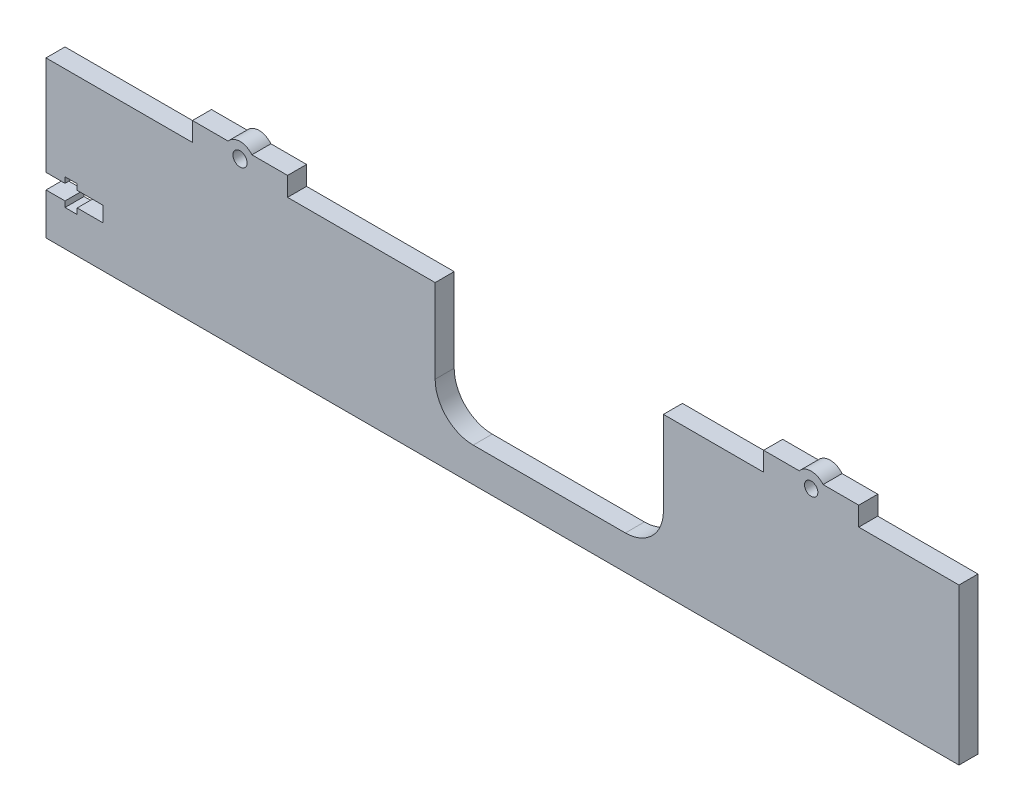
SolidWorks part; units mm, degrees
ref_plane "Front Plane" through (0, 0, 0) normal (0, 0, 1) x (1, 0, 0)
ref_plane "Top Plane" through (0, 0, 0) normal (0, 1, 0) x (1, 0, 0)
ref_plane "Right Plane" through (0, 0, 0) normal (1, 0, 0) x (0, 0, -1)
sketch "Sketch1" plane through (0, 0, 0) normal (0, 0, 1) x (1, 0, 0)
  line L1 (-120, 25.5) -> (120, 25.5)
  line L2 (-120, 25.5) -> (-120, -25.5)
  line L3 (-120, -25.5) -> (120, -25.5)
  line L4 (120, 25.5) -> (120, -25.5)
  dimension "D1" = 240
  dimension "D2" = 51
  dimension "D3" = 25.5
  dimension "D4" = 120
extrude "Boss-Extrude1" add sketch "Sketch1" along normal blind 5
sketch "Sketch4" plane through (0, 0, 5) normal (0, 0, 1) x (1, 0, 0)
  line L0 (120, 25.5) -> (-120, 25.5) construction
  line L1 (-81.5, 25.5) -> (-56.5, 25.5)
  line L2 (-81.5, 25.5) -> (-81.5, 30.5)
  line L3 (-81.5, 30.5) -> (-56.5, 30.5)
  line L4 (-56.5, 25.5) -> (-56.5, 30.5)
  line L5 (-120, 25.5) -> (-120, -25.5) construction
  dimension "D1" = 38.5
  dimension "D2" = 25
  dimension "D3" = 5
extrude "Boss-Extrude2" add sketch "Sketch4" against normal blind 5
sketch "Sketch5" plane through (0, 0, 5) normal (0, 0, 1) x (1, 0, 0)
  line L0 (-120, -25.5) -> (120, -25.5) construction
  line L1 (17.5, -25.5) -> (67.5, -25.5)
  line L2 (17.5, -25.5) -> (17.5, -30.5)
  line L3 (17.5, -30.5) -> (67.5, -30.5)
  line L4 (67.5, -25.5) -> (67.5, -30.5)
  line L5 (120, -25.5) -> (120, 25.5) construction
  line L11 (0, 0) -> (0, -46.5213) construction
  line L12 (-67.5, -25.5) -> (-67.5, -30.5)
  line L13 (-17.5, -30.5) -> (-67.5, -30.5)
  line L14 (-17.5, -25.5) -> (-17.5, -30.5)
  line L15 (-17.5, -25.5) -> (-67.5, -25.5)
  point P10 (67.5, -28)
  dimension "D1" = 52.5
  dimension "D2" = 50
  dimension "D3" = 5
extrude "Boss-Extrude3" [suppressed] add sketch "Sketch5" against normal blind 5
sketch "Sketch6" plane through (0, 0, 5) normal (0, 0, 1) x (1, 0, 0)
  line L13 (0, 0) -> (0, -13.303) construction
  line L14 (-115, -4.5622) -> (-120, -4.5622)
  line L15 (-111.8, -0.5622) -> (-105, -0.5622)
  line L16 (-111.8, -6.0622) -> (-111.8, -4.5622)
  line L17 (-115, -6.0622) -> (-111.8, -6.0622)
  line L18 (-115, -4.5622) -> (-115, -6.0622)
  line L19 (-115, 0.9378) -> (-115, -0.5622)
  line L20 (-111.8, 0.9378) -> (-115, 0.9378)
  line L21 (-111.8, -0.5622) -> (-111.8, 0.9378)
  line L22 (-120, -4.5622) -> (-120, -0.5622)
  line L23 (-105, -4.5622) -> (-111.8, -4.5622)
  line L24 (-105, -0.5622) -> (-105, -4.5622)
  line L25 (-120, -0.5622) -> (-115, -0.5622)
extrude "Cut-Extrude1" cut sketch "Sketch6" against normal blind 10
sketch "Sketch9" plane through (0, 0, 5) normal (0, 0, 1) x (1, 0, 0)
  line L0 (-72.9229, 7.4171) -> (72.9229, 7.4171) construction
  text T0 "AerobotiX" font "Century Gothic" height in points 60
extrude "Cut-Extrude3" [suppressed] cut sketch "Sketch9" against normal blind 1
sketch "Sketch14" plane through (0, 0, 5) normal (0, 0, 1) x (1, 0, 0)
  line L0 (120, 25.5) -> (-56.5, 25.5) construction
  line L1 (-17.7, 25.5) -> (42.3, 25.5)
  line L2 (-17.7, 25.5) -> (-17.7, 3.5)
  line L3 (-7.7, -6.5) -> (32.3, -6.5)
  line L4 (42.3, 25.5) -> (42.3, 3.5)
  line L5 (-120, 25.5) -> (-120, -0.5622) construction
  arc A0 (32.3, -6.5) -> (42.3, 3.5) centre (32.3, 3.5) ccw
  arc A1 (-17.7, 3.5) -> (-7.7, -6.5) centre (-7.7, 3.5) ccw
  dimension "D4" = 10
  dimension "D1" = 102.3
  dimension "D2" = 60
  dimension "D3" = 32
extrude "Cut-Extrude4" cut sketch "Sketch14" against normal blind 10
sketch "Sketch15" plane through (0, 0, 5) normal (0, 0, 1) x (1, 0, 0)
  line L0 (120, 25.5) -> (42.3, 25.5) construction
  line L1 (68.65, 25.5) -> (93.65, 25.5)
  line L2 (68.65, 25.5) -> (68.65, 30.5)
  line L3 (68.65, 30.5) -> (93.65, 30.5)
  line L4 (93.65, 25.5) -> (93.65, 30.5)
  line L5 (42.3, 3.5) -> (42.3, 25.5) construction
  line L7 (120, 25.5) -> (42.3, 25.5) construction
  dimension "D1" = 25
  dimension "D2" = 26.35
  dimension "D3" = 5
extrude "Boss-Extrude4" add sketch "Sketch15" against normal blind 5
sketch "Sketch17" plane through (0, 0, 5) normal (0, 0, 1) x (1, 0, 0)
  circle A0 centre (-69, 28) radius 1.8639
  circle A1 centre (81.1515, 28) radius 1.7483
extrude "Cut-Extrude5" cut sketch "Sketch17" against normal blind 10
sketch "Sketch18" plane through (0, 0, 5) normal (0, 0, 1) x (1, 0, 0)
  circle A0 centre (81.1515, 28) radius 1.7483
  circle A1 centre (81.1515, 28) radius 4
  circle A2 centre (-69, 28) radius 1.8639
  circle A3 centre (-69, 28) radius 4
  dimension "D1" = 8
  dimension "D2" = 8
extrude "Boss-Extrude5" add sketch "Sketch18" against normal blind 5
sketch "Sketch19" plane through (0, 0, 5) normal (0, 0, 1) x (1, 0, 0)
  line L0 (120, -25.5) -> (120, 25.5) construction
  line L1 (-120, -25.5) -> (120, -25.5)
  line L2 (-120, -25.5) -> (-120, -15.5)
  line L3 (-120, -15.5) -> (120, -15.5)
  line L4 (120, -25.5) -> (120, -15.5)
  dimension "D1" = 10
extrude "Cut-Extrude6" cut sketch "Sketch19" against normal blind 10
sketch "Sketch20" plane through (0, 0, 5) normal (0, 0, 1) x (1, 0, 0)
  line L0 (120, -15.5) -> (-120, -15.5) construction
  line L1 (-17.7, -15.5) -> (120, -15.5)
  line L2 (-17.7, -15.5) -> (-17.7, 42.7558)
  line L3 (-17.7, 42.7558) -> (120, 42.7558)
  line L4 (120, -15.5) -> (120, 42.7558)
extrude "Cut-Extrude7" [suppressed] cut sketch "Sketch20" against normal blind 10
